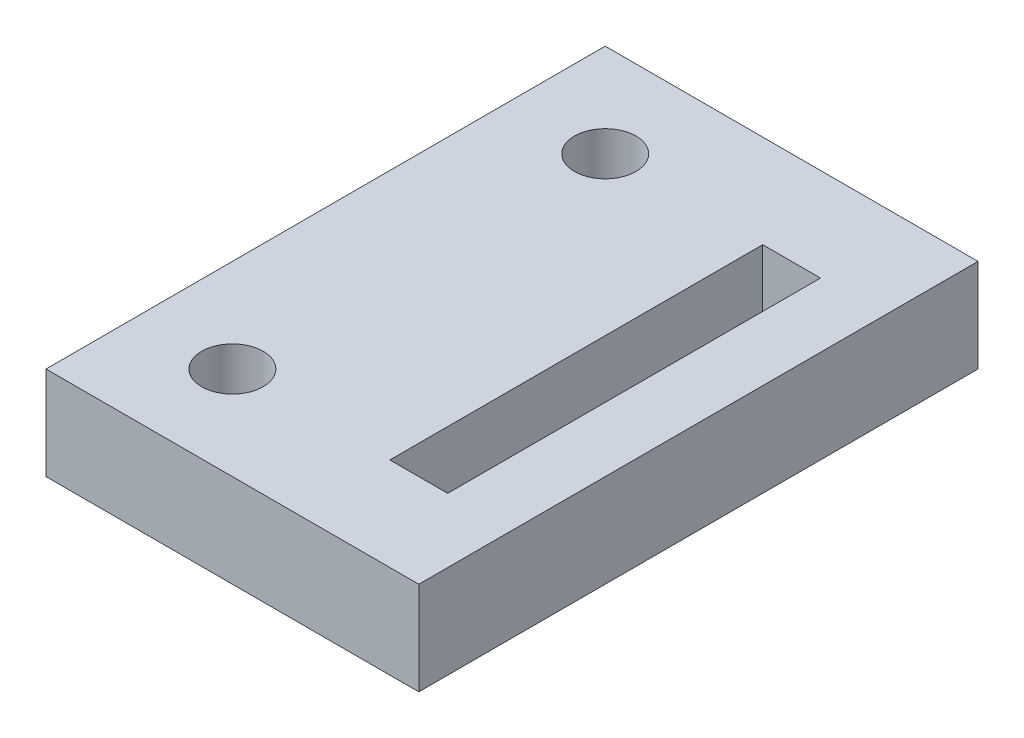
SolidWorks part; units mm, degrees
ref_plane "Front Plane" through (0, 0, 0) normal (0, 0, 1) x (1, 0, 0)
ref_plane "Top Plane" through (0, 0, 0) normal (0, 1, 0) x (1, 0, 0)
ref_plane "Right Plane" through (0, 0, 0) normal (1, 0, 0) x (0, 0, -1)
sketch "Sketch1" plane through (0, 0, 0) normal (0, 1, 0) x (1, 0, 0)
  line L0 (-1000, 15) -> (49000, 15) construction
  line L1 (0, 0) -> (10, 0)
  line L2 (0, 0) -> (0, 30)
  line L3 (0, 30) -> (10, 30)
  line L4 (10, 0) -> (10, 30)
  line L6 (10, 30) -> (20, 30)
  line L7 (10, 30) -> (10, 0)
  line L8 (10, 0) -> (20, 0)
  line L9 (20, 30) -> (20, 0)
  line L10 (13.45, 25) -> (16.55, 25)
  line L11 (13.45, 25) -> (13.45, 5)
  line L12 (13.45, 5) -> (16.55, 5)
  line L13 (16.55, 25) -> (16.55, 5)
  circle A0 centre (5, 5) radius 1.65
  circle A1 centre (5, 25) radius 1.65
  point P8 (5, 0)
  point P12 (0, 15)
  point P19 (16.55, 15)
  point P20 (15, 25)
  point P21 (15, 30)
  dimension "D3" = 3.3
  dimension "D1" = 10
  dimension "D2" = 30
  dimension "D4" = 5
  dimension "D5" = 10
  dimension "D6" = 3.1
  dimension "D7" = 20
extrude "Boss-Extrude1" add sketch "Sketch1" along normal blind 5 contours L2 L0 L7 L3 A1 | L7 L0 L11 L10 L13 L9 L6 | L0 L4 L8 L9 L13 L12 L11 | L0 L2 L1 L4 A0
